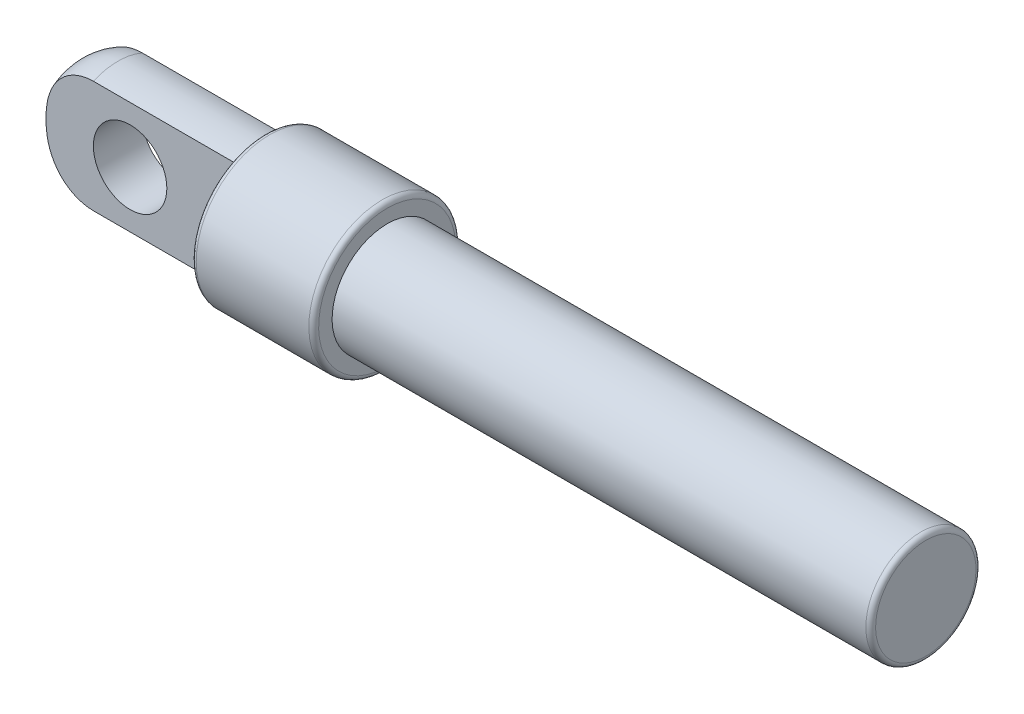
SolidWorks part; units mm, degrees
ref_plane "前视基准面" through (0, 0, 0) normal (0, 0, 1) x (1, 0, 0)
ref_plane "上视基准面" through (0, 0, 0) normal (0, 1, 0) x (1, 0, 0)
ref_plane "右视基准面" through (0, 0, 0) normal (1, 0, 0) x (0, 0, -1)
sketch "草图1" plane through (0, 0, 0) normal (0, 0, 1) x (1, 0, 0)
  line L0 (0, 0) -> (-9, 0) construction
  line L1 (0, 0) -> (0, 2.25)
  line L2 (0, 2.25) -> (-22, 2.25)
  line L3 (-22, 2.25) -> (-22, 3)
  line L4 (-22, 3) -> (-27, 3)
  line L5 (-27, 3) -> (-27, 2.5)
  line L6 (-27, 2.5) -> (-35, 2.5)
  line L7 (-35, 2.5) -> (-35, 0)
  line L8 (-35, 0) -> (0, 0)
  dimension "D1" = 4.5
  dimension "D2" = 6
  dimension "D3" = 5
  dimension "D4" = 22
  dimension "D5" = 5
  dimension "D6" = 35
revolve "旋转1" add sketch "草图1" angle 360 about L0
fillet "圆角1" radius 2 1 edges at (-35, 2.5, 0)
sketch "草图2" plane through (-35, 0, 0) normal (-1, 0, 0) x (0, 0, 1)
  line L1 (-1, 5.8028) -> (1, 5.8028)
  line L2 (-1, 5.8028) -> (-1, -6.1588)
  line L3 (-1, -6.1588) -> (1, -6.1588)
  line L4 (1, 5.8028) -> (1, -6.1588)
  circle A0 centre (0, 0) radius 7.3214
  point P4 (0, 5.8028)
  dimension "D1" = 2
extrude "切除-拉伸1" cut sketch "草图2" against normal blind 8
sketch "草图3" plane through (0, 0, -1) normal (0, 0, -1) x (-1, 0, 0)
  line L0 (51, 2) -> (51, -2) construction
  line L1 (35, -0.5) -> (35, 0.5) construction
  circle A0 centre (31.5, 0) radius 1.5
  point P4 (51, 0)
  dimension "D1" = 3
  dimension "D2" = 3.5
extrude "切除-拉伸2" cut sketch "草图3" against normal up to surface (2 mm away) up to face at (-29.5253, 0.1305, 1)
fillet "圆角2" radius 0.2 3 edges at (-22, 3, 0) (-27, 3, 0) (0, 2.25, 0)
